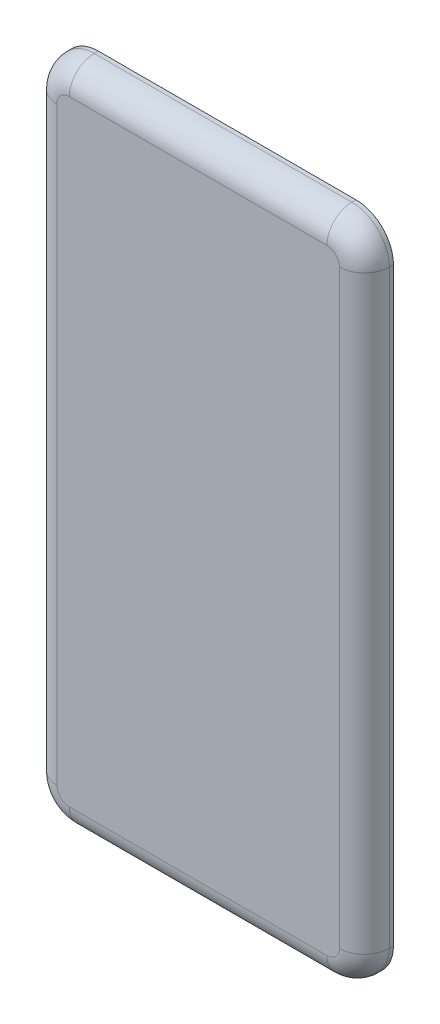
SolidWorks part; units mm, degrees
ref_plane "前视基准面" through (0, 0, 0) normal (0, 0, 1) x (1, 0, 0)
ref_plane "上视基准面" through (0, 0, 0) normal (0, 1, 0) x (1, 0, 0)
ref_plane "右视基准面" through (0, 0, 0) normal (1, 0, 0) x (0, 0, -1)
sketch "草图1" plane through (0, 0, 0) normal (0, 0, 1) x (1, 0, 0)
  line L0 (48.1929, 0) -> (48.1929, 80)
  line L1 (48.1929, 80) -> (88.1929, 80)
  line L2 (88.1929, 80) -> (88.1929, 0)
  line L3 (88.1929, 0) -> (48.1929, 0)
extrude "凸台-拉伸1" add sketch "草图1" along normal blind 3.5
fillet "圆角1" radius 4.5 4 edges at (48.1929, 0, 1.75) (88.1929, 0, 1.75) (48.1929, 80, 1.75) (88.1929, 80, 1.75)
fillet "圆角2" radius 3 8 edges at (49.5109, 78.682, 3.5) (68.1929, 80, 3.5) (86.8749, 78.682, 3.5) (88.1929, 40, 3.5) (86.8749, 1.318, 3.5) (68.1929, 0, 3.5) (49.5109, 1.318, 3.5) (48.1929, 40, 3.5)
